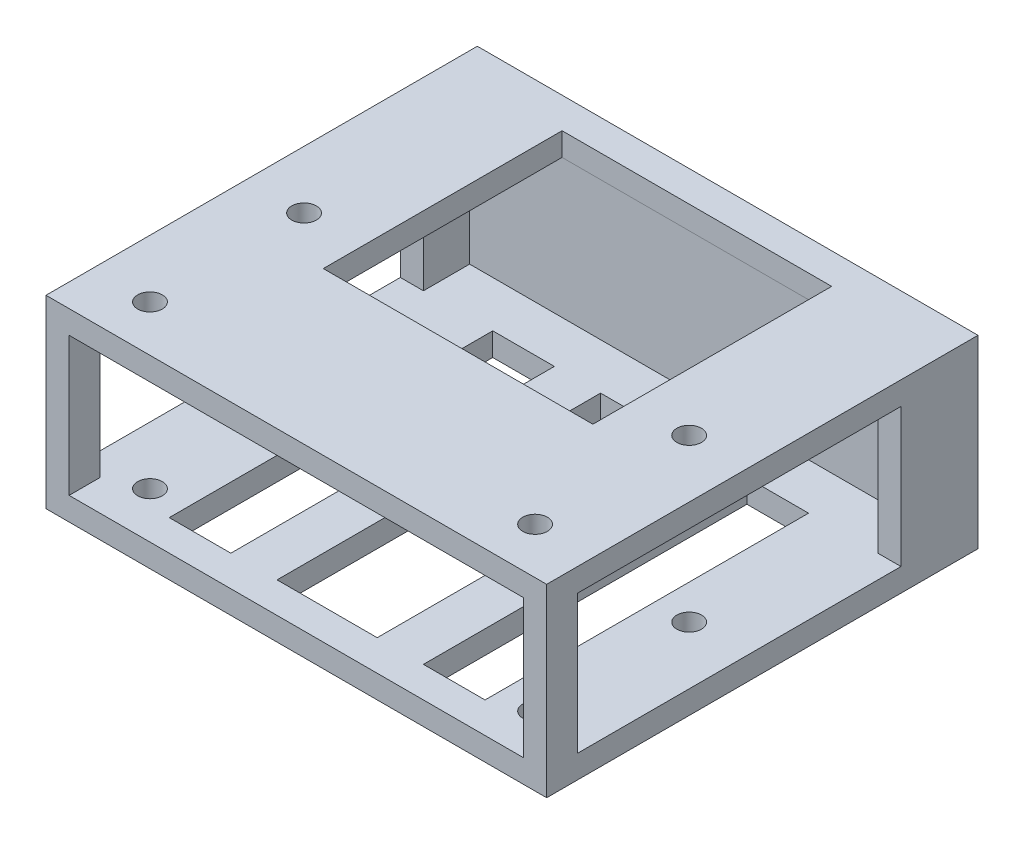
SolidWorks part; units mm, degrees
ref_plane "前视基准面" through (0, 0, 0) normal (0, 0, 1) x (1, 0, 0)
ref_plane "上视基准面" through (0, 0, 0) normal (0, 1, 0) x (1, 0, 0)
ref_plane "右视基准面" through (0, 0, 0) normal (1, 0, 0) x (0, 0, -1)
other "Configuration Table"
sketch "草图1" plane through (0, 0, 0) normal (0, 0, 1) x (1, 0, 0)
  line L1 (-29.5, -9) -> (29.5, -9)
  line L2 (-29.5, -9) -> (-29.5, 9)
  line L3 (-29.5, 9) -> (29.5, 9)
  line L4 (29.5, -9) -> (29.5, 9)
  line L5 (-29.5, -9) -> (29.5, 9) construction
  line L6 (-29.5, 9) -> (29.5, -9) construction
  point P0 (0, 0)
  dimension "D1" = 59
  dimension "D2" = 18
extrude "凸台-拉伸1" add sketch "草图1" along normal blind 4
sketch "草图2" plane through (0, 0, 0) normal (0, 0, -1) x (-1, 0, 0)
  line L0 (-29.5, 9) -> (29.5, 9) construction
  line L1 (-32.5, -12) -> (32.5, -12)
  line L2 (-32.5, -12) -> (-32.5, 12)
  line L3 (-32.5, 12) -> (32.5, 12)
  line L4 (32.5, -12) -> (32.5, 12)
  line L5 (-32.5, -12) -> (32.5, 12) construction
  line L6 (-32.5, 12) -> (32.5, -12) construction
  line L7 (-29.5, -9) -> (-29.5, 9) construction
  line L8 (29.5, 9) -> (29.5, -9) construction
  line L9 (29.5, -9) -> (-29.5, -9) construction
  line L10 (29.5, 9) -> (29.5, -9)
  line L11 (29.5, -9) -> (-29.5, -9)
  line L12 (-29.5, -9) -> (-29.5, 9)
  line L13 (-29.5, 9) -> (29.5, 9)
  point P0 (0, 0)
  dimension "D1" = 3
  dimension "D2" = 3
extrude "凸台-拉伸3" add sketch "草图2" against normal blind 56 separate body
sketch "草图3" plane through (0, 12, 0) normal (0, 1, 0) x (1, 0, 0)
  line L1 (-32.5, 0) -> (32.5, 0) construction
  line L2 (-17.5, -4) -> (-17.5, -35)
  line L4 (-17.5, -35) -> (17.5, -35)
  line L5 (17.5, -35) -> (17.5, -4)
  line L6 (-17.5, -4) -> (17.5, -4)
  point P6 (0, 0)
  dimension "D1" = 35
  dimension "D2" = 4
  dimension "D3" = 31
extrude "切除-拉伸1" cut sketch "草图3" against normal up to next (3 mm away)
sketch "草图4" plane through (0, -12, 0) normal (0, -1, 0) x (1, 0, 0)
  circle A0 centre (25, 50) radius 1.6
  circle A1 centre (25, 30) radius 1.6
  circle A2 centre (-25, 30) radius 1.6
  circle A3 centre (-25, 50) radius 1.6
  dimension "D1" = 3.2
extrude "切除-拉伸2" cut sketch "草图4" against normal through all
sketch "草图5" plane through (32.5, 0, 0) normal (1, 0, 0) x (0, 0, -1)
  line L0 (-56, -9) -> (0, -9) construction
  line L1 (-52, -9) -> (-10, -9)
  line L2 (-52, -9) -> (-52, 9)
  line L3 (-52, 9) -> (-10, 9)
  line L4 (-10, -9) -> (-10, 9)
  line L5 (-56, 9) -> (0, 9) construction
  line L6 (-56, 12) -> (-56, -12) construction
  dimension "D1" = 4
extrude "切除-拉伸3" cut sketch "草图5" against normal through all
sketch "草图6" plane through (0, -12, 0) normal (0, -1, 0) x (1, 0, 0)
  line L0 (32.5, 0) -> (-32.5, 0) construction
  line L1 (-6.5, 10) -> (6.5, 10)
  line L2 (-6.5, 10) -> (-6.5, 52)
  line L3 (-6.5, 52) -> (6.5, 52)
  line L4 (6.5, 10) -> (6.5, 52)
  line L5 (-6.5, 10) -> (6.5, 52) construction
  line L6 (-6.5, 52) -> (6.5, 10) construction
  line L7 (32.5, 56) -> (-32.5, 56) construction
  line L9 (20.5, 10) -> (12.5, 10)
  line L10 (20.5, 10) -> (20.5, 52)
  line L11 (20.5, 52) -> (12.5, 52)
  line L12 (12.5, 10) -> (12.5, 52)
  line L13 (-20.5, 10) -> (-12.5, 10)
  line L14 (-20.5, 10) -> (-20.5, 52)
  line L15 (-20.5, 52) -> (-12.5, 52)
  line L16 (-12.5, 10) -> (-12.5, 52)
  point P0 (0, 31)
  point P17 (20.5, 59.5756)
  point P18 (-20.5, 10)
  point P19 (20.5, 10)
  dimension "D1" = 10
  dimension "D2" = 4
  dimension "D3" = 8
  dimension "D4" = 8
  dimension "D5" = 6
  dimension "D6" = 6
extrude "切除-拉伸4" cut sketch "草图6" against normal up to next (3 mm away)
